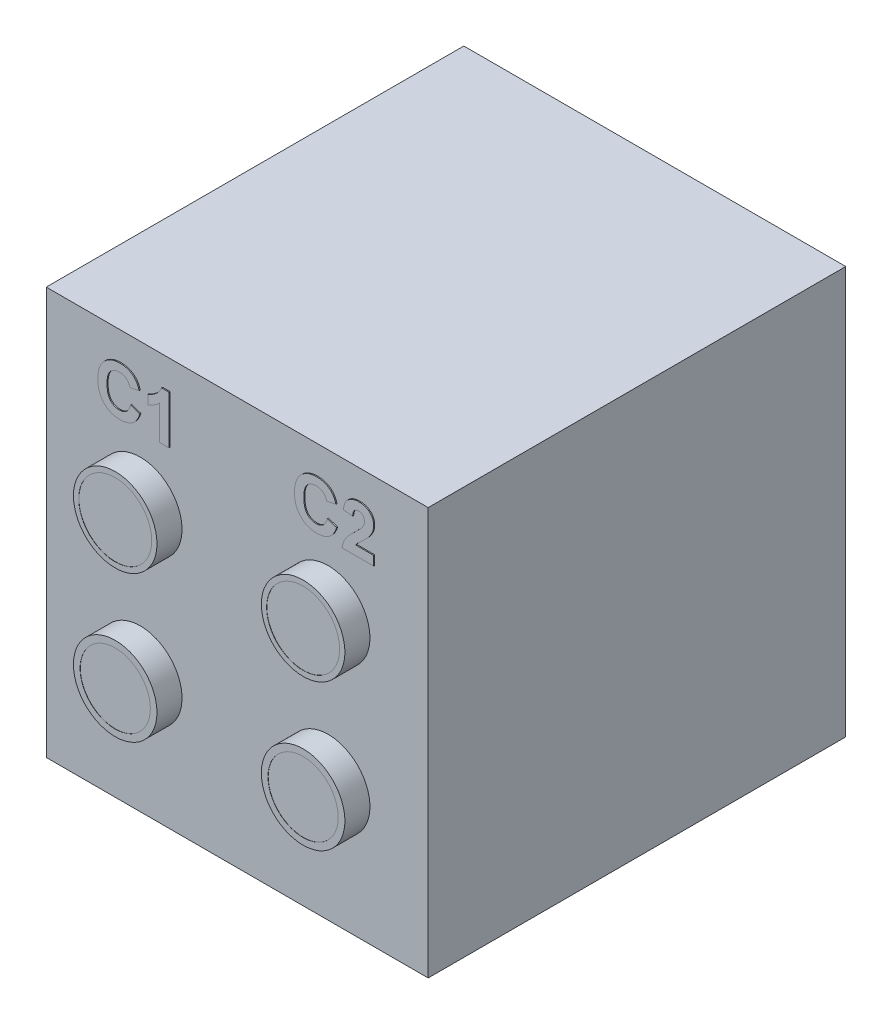
SolidWorks part; units mm, degrees
ref_plane "Alzado" through (0, 0, 0) normal (0, 0, 1) x (1, 0, 0)
ref_plane "Planta" through (0, 0, 0) normal (0, 1, 0) x (1, 0, 0)
ref_plane "Vista lateral" through (0, 0, 0) normal (1, 0, 0) x (0, 0, -1)
sketch "Croquis1" plane through (0, 0, 0) normal (0, 0, 1) x (1, 0, 0)
  line L1 (0, 0) -> (400, 0)
  line L2 (0, 0) -> (0, 500)
  line L3 (0, 500) -> (400, 500)
  line L4 (400, 0) -> (400, 500)
  dimension "D1" = 400
  dimension "D2" = 500
extrude "Saliente-Extruir1" add sketch "Croquis1" along normal blind 200
sketch "Croquis3" plane through (0, 0, 200) normal (0, 0, 1) x (1, 0, 0)
  line L0 (200, 500) -> (200, 440) construction
  line L1 (400, 500) -> (0, 500) construction
  line L3 (137.5, 440.5) -> (262.5, 440.5)
  line L4 (137.5, 440.5) -> (137.5, 499.5)
  line L5 (137.5, 499.5) -> (262.5, 499.5)
  line L6 (262.5, 440.5) -> (262.5, 499.5)
  line L7 (137.5, 440.5) -> (262.5, 499.5) construction
  line L8 (137.5, 499.5) -> (262.5, 440.5) construction
  point P4 (200, 470)
  dimension "D1" = 60
  dimension "D2" = 59
  dimension "D3" = 125
extrude "Saliente-Extruir4" add sketch "Croquis3" along normal blind 30
fillet "Redondeo1" radius 6 4 edges at (200, 440.5, 230) (262.5, 470, 230) (137.5, 470, 230) (200, 499.5, 230)
fillet "Redondeo2" radius 3 8 edges at (139.2574, 442.2574, 228.2426) (139.2574, 497.7426, 228.2426) (260.7426, 442.2574, 228.2426) (260.7426, 497.7426, 228.2426) (137.5, 440.5, 212) (137.5, 499.5, 212) (262.5, 440.5, 212) (262.5, 499.5, 212)
sketch "Croquis4" plane through (0, 0, 200) normal (0, 0, 1) x (1, 0, 0)
  line L0 (0, 500) -> (0, 0) construction
  circle A0 centre (25, 250) radius 10
  dimension "D1" = 20
  dimension "D2" = 25
extrude "Saliente-Extruir5" add sketch "Croquis4" along normal blind 4
chamfer "Chaflán1" distance 2 angle 45 1 edges at (35, 250, 204)
sketch "Croquis5" plane through (0, 0, 204) normal (0, 0, 1) x (1, 0, 0)
  line L1 (23.5545, 244.0789) -> (26.4455, 244.0789)
  line L2 (23.5545, 244.0789) -> (23.5545, 255.9211)
  line L3 (23.5545, 255.9211) -> (26.4455, 255.9211)
  line L4 (26.4455, 244.0789) -> (26.4455, 255.9211)
  line L5 (23.5545, 244.0789) -> (26.4455, 255.9211) construction
  line L6 (23.5545, 255.9211) -> (26.4455, 244.0789) construction
  point P0 (25, 250)
extrude "Cortar-Extruir1" cut sketch "Croquis5" against normal blind 0.1
sketch "Croquis6" plane through (0, 0, 200) normal (0, 0, 1) x (1, 0, 0)
  line L0 (66.8377, 94.0486) -> (111.8377, 94.0486) construction
  line L1 (111.8377, 94.0486) -> (111.8377, 185.8496) construction
  line L2 (66.8377, 164.0486) -> (66.8377, 94.0486) construction
  line L3 (156.8377, 164.0486) -> (156.8377, 94.0486) construction
  circle A0 centre (66.8377, 164.0486) radius 20
  circle A1 centre (66.8377, 94.0486) radius 20
  circle A2 centre (156.8377, 94.0486) radius 20
  circle A3 centre (156.8377, 164.0486) radius 20
  dimension "D1" = 40
  dimension "D2" = 40
  dimension "D3" = 70
  dimension "D4" = 45
extrude "Saliente-Extruir6" add sketch "Croquis6" along normal blind 12
sketch "Croquis7" plane through (0, 0, 212) normal (0, 0, 1) x (1, 0, 0)
  line L0 (66.8377, 94.0486) -> (111.8377, 94.0486) construction
  line L1 (111.8377, 94.0486) -> (111.8377, 186.5162) construction
  circle A0 centre (66.8377, 164.0486) radius 17.4894
  circle A1 centre (66.8377, 94.0486) radius 16.8232
  circle A2 centre (156.8377, 94.0486) radius 16.8232
  circle A3 centre (156.8377, 164.0486) radius 17.4894
  dimension "D1" = 45
extrude "Cortar-Extruir2" cut sketch "Croquis7" against normal blind 0.1
sketch "Croquis8" plane through (0, 0, 0) normal (-1, 0, 0) x (0, 0, 1)
  line L0 (100, 500) -> (100, 440) construction
  line L1 (200, 500) -> (0, 500) construction
  line L3 (37.5, 440.5) -> (162.5, 440.5)
  line L4 (37.5, 440.5) -> (37.5, 499.5)
  line L5 (37.5, 499.5) -> (162.5, 499.5)
  line L6 (162.5, 440.5) -> (162.5, 499.5)
  line L7 (37.5, 440.5) -> (162.5, 499.5) construction
  line L8 (37.5, 499.5) -> (162.5, 440.5) construction
  point P4 (100, 470)
  dimension "D1" = 60
  dimension "D2" = 59
  dimension "D3" = 125
extrude "Saliente-Extruir7" add sketch "Croquis8" along normal blind 30
fillet "Redondeo3" radius 5 4 edges at (-30, 440.5, 100) (-30, 470, 162.5) (-30, 499.5, 100) (-30, 470, 37.5)
fillet "Redondeo4" radius 4 8 edges at (-28.5355, 441.9645, 38.9645) (-28.5355, 441.9645, 161.0355) (-28.5355, 498.0355, 38.9645) (-28.5355, 498.0355, 161.0355) (-12.5, 440.5, 37.5) (-12.5, 440.5, 162.5) (-12.5, 499.5, 37.5) (-12.5, 499.5, 162.5)
sketch "Croquis9" plane through (0, 0, 230) normal (0, 0, 1) x (1, 0, 0)
  line L0 (400, 500) -> (0, 500) construction
  line L1 (124.3403, 500) -> (275.1533, 500)
  line L2 (124.3403, 500) -> (124.3403, 434.3766)
  line L3 (124.3403, 434.3766) -> (275.1533, 434.3766)
  line L4 (275.1533, 500) -> (275.1533, 434.3766)
extrude "Cortar-Extruir3" cut sketch "Croquis9" against normal up to surface (30 mm away)
sketch "Croquis10" plane through (0, 0, 200) normal (0, 0, 1) x (1, 0, 0)
  line L0 (400, 500) -> (0, 500) construction
  line L1 (172.2, 420) -> (350, 420)
  line L2 (172.2, 420) -> (172.2, 320)
  line L3 (172.2, 320) -> (350, 320)
  line L4 (350, 420) -> (350, 320)
  line L5 (400, 0) -> (400, 500) construction
  dimension "D1" = 177.8
  dimension "D2" = 100
  dimension "D3" = 80
  dimension "D4" = 50
extrude "Saliente-Extruir8" add sketch "Croquis10" along normal blind 5
fillet "Redondeo5" radius 3 4 edges at (350, 320, 202.5) (350, 420, 202.5) (172.2, 320, 202.5) (172.2, 420, 202.5)
fillet "Redondeo6" radius 0.5 8 edges at (349.1213, 419.1213, 205) (350, 370, 205) (349.1213, 320.8787, 205) (261.1, 320, 205) (173.0787, 320.8787, 205) (172.2, 370, 205) (173.0787, 419.1213, 205) (261.1, 420, 205)
sketch "Croquis11" plane through (0, 0, 205) normal (0, 0, 1) x (1, 0, 0)
  line L0 (261.1, 419.5) -> (261.1, 320.5) construction
  line L1 (347, 419.5) -> (175.2, 419.5) construction
  line L2 (175.2, 320.5) -> (347, 320.5) construction
  line L4 (333.765, 331.03) -> (188.435, 331.03)
  line L5 (333.765, 331.03) -> (333.765, 408.97)
  line L6 (333.765, 408.97) -> (188.435, 408.97)
  line L7 (188.435, 331.03) -> (188.435, 408.97)
  line L8 (333.765, 331.03) -> (188.435, 408.97) construction
  line L9 (333.765, 408.97) -> (188.435, 331.03) construction
  point P6 (261.1, 370)
extrude "Cortar-Extruir4" cut sketch "Croquis11" against normal blind 2
sketch "Croquis12" plane through (-30, 0, 0) normal (-1, 0, 0) x (0, 0, 1)
  line L0 (200, 500) -> (0, 500) construction
  line L1 (24.5305, 500) -> (179.0417, 500)
  line L2 (24.5305, 500) -> (24.5305, 435.4134)
  line L3 (24.5305, 435.4134) -> (179.0417, 435.4134)
  line L4 (179.0417, 500) -> (179.0417, 435.4134)
extrude "Cortar-Extruir5" cut sketch "Croquis12" against normal up to surface (30 mm away)
sketch "Croquis14" plane through (0, 0, 200) normal (0, 0, 1) x (1, 0, 0)
  line L0 (45.4888, 195.2188) -> (197.1907, 195.2188) construction
  text T0 "C1      C2" font "Arial" height in points 90
extrude "Saliente-Extruir9" add sketch "Croquis14" along normal blind 0.5
sketch "Croquis15" plane through (0, 0, 200) normal (0, 0, 1) x (1, 0, 0)
  line L1 (21.8097, 232.0455) -> (204.7427, 232.0455)
  line L2 (21.8097, 232.0455) -> (21.8097, 36.9169)
  line L3 (21.8097, 36.9169) -> (204.7427, 36.9169)
  line L4 (204.7427, 232.0455) -> (204.7427, 36.9169)
  line L5 (-258.3352, -321.049) -> (484.8876, -321.049)
  line L6 (-258.3352, -321.049) -> (-258.3352, 590.0114)
  line L7 (-258.3352, 590.0114) -> (484.8876, 590.0114)
  line L8 (484.8876, -321.049) -> (484.8876, 590.0114)
  line L9 (-258.3352, -321.049) -> (484.8876, 590.0114) construction
  line L10 (-258.3352, 590.0114) -> (484.8876, -321.049) construction
  point P4 (113.2762, 134.4812)
extrude "Cortar-Extruir6" cut sketch "Croquis15" against normal mid plane 600
